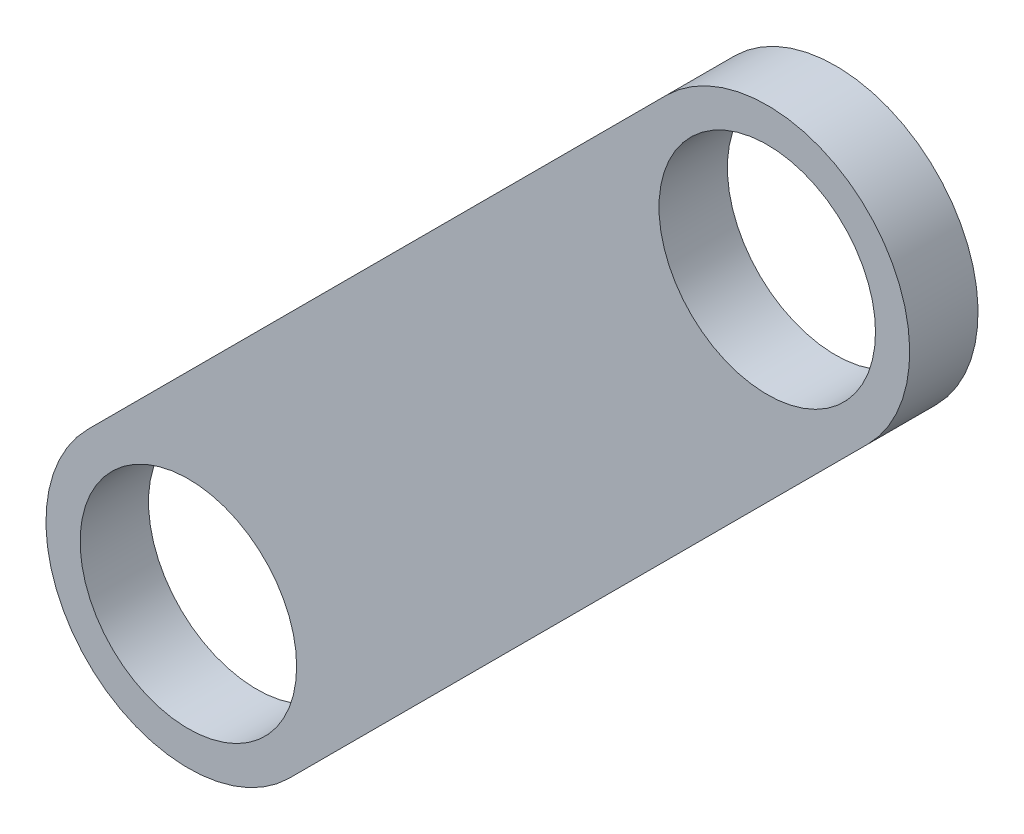
SolidWorks part; units mm, degrees
ref_plane "Front Plane" through (0, 0, 0) normal (0, 0, 1) x (1, 0, 0)
ref_plane "Top Plane" through (0, 0, 0) normal (0, 1, 0) x (1, 0, 0)
ref_plane "Right Plane" through (0, 0, 0) normal (1, 0, 0) x (0, 0, -1)
sketch "Sketch1" plane through (0, 0, 0) normal (0, 0, 1) x (1, 0, 0)
  line L0 (0, 0) -> (50.8, 50.8) construction
  line L1 (-8.8388, 8.8388) -> (41.9612, 59.6388)
  line L2 (8.8388, -8.8388) -> (59.6388, 41.9612)
  arc A0 (-8.8388, 8.8388) -> (8.8388, -8.8388) centre (0, 0) ccw
  arc A1 (59.6388, 41.9612) -> (41.9612, 59.6388) centre (50.8, 50.8) ccw
  circle A2 centre (0, 0) radius 9.5
  circle A3 centre (50.8, 50.8) radius 9.5
  point P0 (0, 0)
  point P1 (50.8, 50.8)
  point P5 (25.4, 25.4)
  dimension "D3" = 12.5
  dimension "D4" = 19
  dimension "D5" = 19
  dimension "D1" = 50.8
  dimension "D2" = 50.8
extrude "Boss-Extrude1" add sketch "Sketch1" along normal blind 6
equation "\"D5@Sketch1\"=\"D4@Sketch1\""
